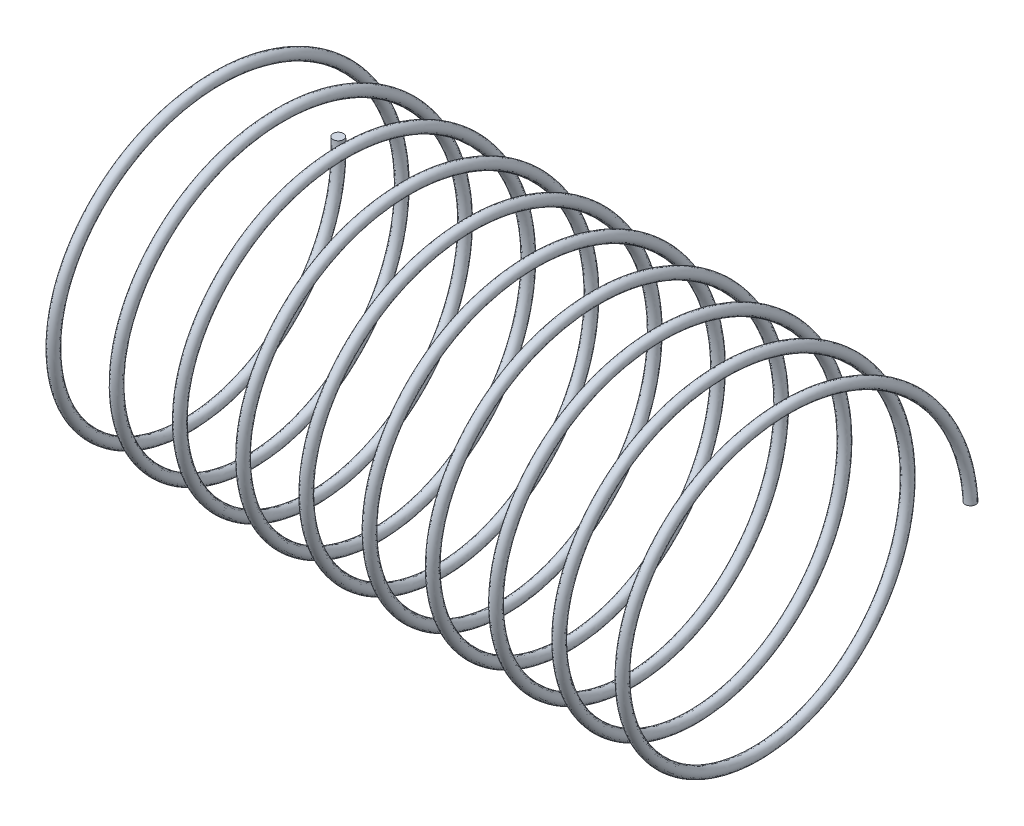
SolidWorks part; units mm, degrees
ref_plane "Plan de face" through (0, 0, 0) normal (0, 0, 1) x (1, 0, 0)
ref_plane "Plan de dessus" through (0, 0, 0) normal (0, 1, 0) x (1, 0, 0)
ref_plane "Plan de droite" through (0, 0, 0) normal (1, 0, 0) x (0, 0, -1)
sketch "Sketch1" plane through (0, 0, 0) normal (1, 0, 0) x (0, 0, -1)
  circle A0 centre (0, 0) radius 3
curve "Helix/Spiral1" pitch 1.2 height 12 turns 10
sketch "Sketch4" plane through (0, 0, 0) normal (0, 1, 0) x (1, 0, 0)
  circle A0 centre (0, 3) radius 0.1
  spline S0 degree 3 poles (0, 3) (0.0248, 3) (0.0751, 2.8438) (0.15, 2.1765) (0.225, 1.1779) (0.3, 0) (0.375, -1.1779) (0.45, -2.1765) (0.525, -2.8438) (0.6, -3.0781) (0.675, -2.8438) (0.75, -2.1765) (0.825, -1.1779) (0.9, 0) (0.975, 1.1779) (1.05, 2.1765) (1.125, 2.8438) (1.2, 3.0781) (1.275, 2.8438) (1.35, 2.1765) (1.425, 1.1779) (1.5, 0) (1.575, -1.1779) (1.65, -2.1765) (1.725, -2.8438) (1.8, -3.0781) (1.875, -2.8438) (1.95, -2.1765) (2.025, -1.1779) (2.1, 0) (2.175, 1.1779) (2.25, 2.1765) (2.325, 2.8438) (2.4, 3.0781) (2.475, 2.8438) (2.55, 2.1765) (2.625, 1.1779) (2.7, 0) (2.775, -1.1779) (2.85, -2.1765) (2.925, -2.8438) (3, -3.0781) (3.075, -2.8438) (3.15, -2.1765) (3.225, -1.1779) (3.3, 0) (3.375, 1.1779) (3.45, 2.1765) (3.525, 2.8438) (3.6, 3.0781) (3.675, 2.8438) (3.75, 2.1765) (3.825, 1.1779) (3.9, 0) (3.975, -1.1779) (4.05, -2.1765) (4.125, -2.8438) (4.2, -3.0781) (4.275, -2.8438) (4.35, -2.1765) (4.425, -1.1779) (4.5, 0) (4.575, 1.1779) (4.65, 2.1765) (4.725, 2.8438) (4.8, 3.0781) (4.875, 2.8438) (4.95, 2.1765) (5.025, 1.1779) (5.1, 0) (5.175, -1.1779) (5.25, -2.1765) (5.325, -2.8438) (5.4, -3.0781) (5.475, -2.8438) (5.55, -2.1765) (5.625, -1.1779) (5.7, 0) (5.775, 1.1779) (5.85, 2.1765) (5.925, 2.8438) (6, 3.0781) (6.075, 2.8438) (6.15, 2.1765) (6.225, 1.1779) (6.3, 0) (6.375, -1.1779) (6.45, -2.1765) (6.525, -2.8438) (6.6, -3.0781) (6.675, -2.8438) (6.75, -2.1765) (6.825, -1.1779) (6.9, 0) (6.975, 1.1779) (7.05, 2.1765) (7.125, 2.8438) (7.2, 3.0781) (7.275, 2.8438) (7.35, 2.1765) (7.425, 1.1779) (7.5, 0) (7.575, -1.1779) (7.65, -2.1765) (7.725, -2.8438) (7.8, -3.0781) (7.875, -2.8438) (7.95, -2.1765) (8.025, -1.1779) (8.1, 0) (8.175, 1.1779) (8.25, 2.1765) (8.325, 2.8438) (8.4, 3.0781) (8.475, 2.8438) (8.55, 2.1765) (8.625, 1.1779) (8.7, 0) (8.775, -1.1779) (8.85, -2.1765) (8.925, -2.8438) (9, -3.0781) (9.075, -2.8438) (9.15, -2.1765) (9.225, -1.1779) (9.3, 0) (9.375, 1.1779) (9.45, 2.1765) (9.525, 2.8438) (9.6, 3.0781) (9.675, 2.8438) (9.75, 2.1765) (9.825, 1.1779) (9.9, 0) (9.975, -1.1779) (10.05, -2.1765) (10.125, -2.8438) (10.2, -3.0781) (10.275, -2.8438) (10.35, -2.1765) (10.425, -1.1779) (10.5, 0) (10.575, 1.1779) (10.65, 2.1765) (10.725, 2.8438) (10.8, 3.0781) (10.875, 2.8438) (10.95, 2.1765) (11.025, 1.1779) (11.1, 0) (11.175, -1.1779) (11.25, -2.1765) (11.325, -2.8438) (11.4, -3.0781) (11.475, -2.8438) (11.55, -2.1765) (11.625, -1.1779) (11.7, 0) (11.775, 1.1779) (11.85, 2.1765) (11.9249, 2.8438) (11.9752, 3) (12, 3) knots 0 0 0 0 0.00625 0.0125 0.01875 0.025 0.03125 0.0375 0.04375 0.05 0.05625 0.0625 0.06875 0.075 0.08125 0.0875 0.09375 0.1 0.10625 0.1125 0.11875 0.125 0.13125 0.1375 0.14375 0.15 0.15625 0.1625 0.16875 0.175 0.18125 0.1875 0.19375 0.2 0.20625 0.2125 0.21875 0.225 0.23125 0.2375 0.24375 0.25 0.25625 0.2625 0.26875 0.275 0.28125 0.2875 0.29375 0.3 0.30625 0.3125 0.31875 0.325 0.33125 0.3375 0.34375 0.35 0.35625 0.3625 0.36875 0.375 0.38125 0.3875 0.39375 0.4 0.40625 0.4125 0.41875 0.425 0.43125 0.4375 0.44375 0.45 0.45625 0.4625 0.46875 0.475 0.48125 0.4875 0.49375 0.5 0.50625 0.5125 0.51875 0.525 0.53125 0.5375 0.54375 0.55 0.55625 0.5625 0.56875 0.575 0.58125 0.5875 0.59375 0.6 0.60625 0.6125 0.61875 0.625 0.63125 0.6375 0.64375 0.65 0.65625 0.6625 0.66875 0.675 0.68125 0.6875 0.69375 0.7 0.70625 0.7125 0.71875 0.725 0.73125 0.7375 0.74375 0.75 0.75625 0.7625 0.76875 0.775 0.78125 0.7875 0.79375 0.8 0.80625 0.8125 0.81875 0.825 0.83125 0.8375 0.84375 0.85 0.85625 0.8625 0.86875 0.875 0.88125 0.8875 0.89375 0.9 0.90625 0.9125 0.91875 0.925 0.93125 0.9375 0.94375 0.95 0.95625 0.9625 0.96875 0.975 0.98125 0.9875 0.99375 1 1 1 1 construction
sweep "Sweep1" add profiles "Sketch4" path "Helix/Spiral1"
